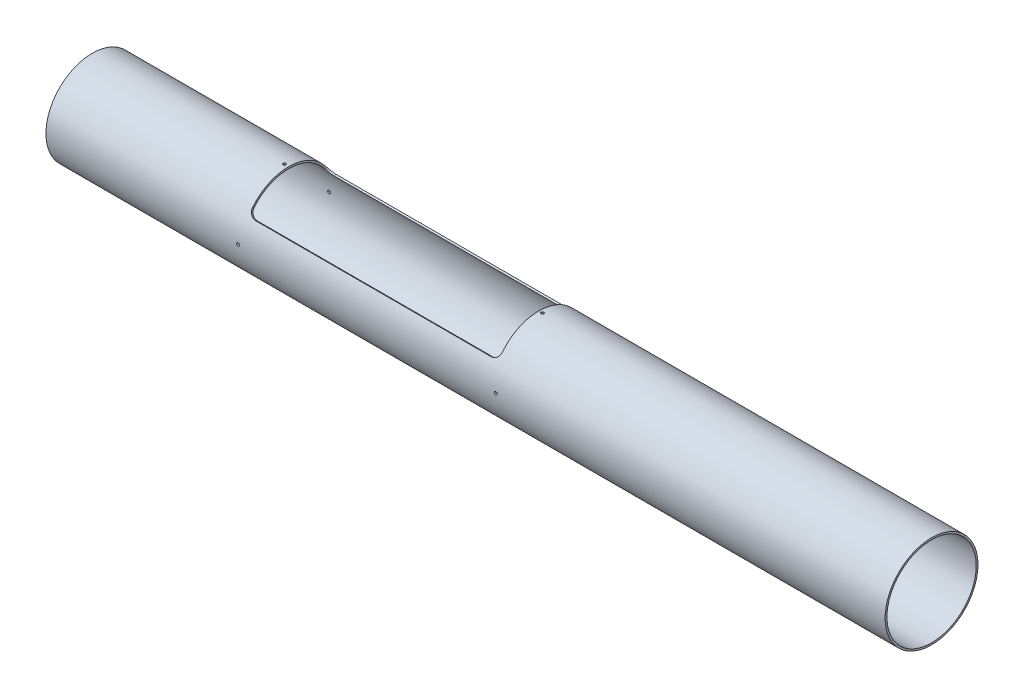
SolidWorks part; units mm, degrees
material "E-Glass Fiber"
ref_plane "Ön Düzlem" through (0, 0, 0) normal (0, 0, 1) x (1, 0, 0)
ref_plane "Üst Düzlem" through (0, 0, 0) normal (0, 1, 0) x (1, 0, 0)
ref_plane "Sağ Düzlem" through (0, 0, 0) normal (1, 0, 0) x (0, 0, -1)
sketch "Sketch1" plane through (0, 0, 0) normal (1, 0, 0) x (0, 0, -1)
  circle A0 centre (0, 0) radius 65
  circle A1 centre (0, 0) radius 62.5
  dimension "D1" = 2.5
  dimension "D2" = 130
  dimension "D3" = 125
extrude "Boss-Extrude1" add sketch "Sketch1" along normal mid plane 1175
sketch "Sketch3" plane through (0, 0, 0) normal (1, 0, 0) x (0, 0, -1)
  line L0 (0, -65) -> (0, 65) construction
  line L1 (0, 0) -> (56.2917, 32.5) construction
  line L2 (0, 0) -> (-56.2917, 32.5) construction
  line L5 (-56.2917, 32.5) -> (-54.1266, 31.25)
  line L6 (56.2917, 32.5) -> (54.1266, 31.25)
  circle A0 centre (0, 0) radius 65 construction
  arc A2 (-56.2917, 32.5) -> (56.2917, 32.5) centre (0, 0) cw
  arc A3 (-54.1266, 31.25) -> (54.1266, 31.25) centre (0, 0) cw
  circle A5 centre (0, 0) radius 62.5 construction
  dimension "D1" = 120
  dimension "D3" = 125
  dimension "D4" = 130
  dimension "D2" = 60
extrude "Cut-Extrude1" cut sketch "Sketch3" against normal blind 312.5 and the other way blind 37.5
fillet "Fillet1" radius 10 4 edges at (37.5, 31.875, 55.2091) (37.5, 31.875, -55.2091) (-312.5, 31.875, -55.2091) (-312.5, 31.875, 55.2091)
sketch "Sketch5" plane through (0, 0, 0) normal (0, 1, 0) x (1, 0, 0)
  line L2 (-587.5, 0) -> (-318.5, 0) construction
  line L3 (-587.5, 65) -> (-587.5, -65) construction
  line L5 (-318.5, 0) -> (-312.5, 0) construction
  line L6 (-312.5, 0) -> (37.5, 0) construction
  line L7 (37.5, 50.6215) -> (37.5, -50.6215) construction
  line L8 (37.5, 0) -> (42.5, 0) construction
  line L9 (42.5, 0) -> (587.5, 0) construction
  line L10 (587.5, -65) -> (587.5, 65) construction
  circle A0 centre (-318.5, 0) radius 2
  circle A1 centre (42.5, 0) radius 2
  dimension "D4" = 4
  dimension "D1" = 545
  dimension "D2" = 350
  dimension "D3" = 6
extrude "Cut-Extrude2" cut sketch "Sketch5" against normal mid plane 200
sketch "Sketch6" plane through (0, 0, 0) normal (0, 0, 1) x (1, 0, 0)
  line L0 (-307.5, 0) -> (-318.5, 0) construction
  line L1 (40.5, 65) -> (44.5, 65) construction
  line L3 (42.5, 0) -> (587.5, 0) construction
  line L4 (587.5, -65) -> (587.5, 65) construction
  line L5 (-318.5, 0) -> (-587.5, 0) construction
  line L6 (-587.5, 65) -> (-587.5, -65) construction
  line L7 (42.5, 65) -> (42.5, 0) construction
  line L8 (-320.5, 65) -> (-316.5, 65) construction
  line L9 (-318.5, 65) -> (-318.5, 0) construction
  circle A0 centre (-318.5, 0) radius 2
  circle A1 centre (42.5, 0) radius 2
  point P19 (42.5, 65)
  point P20 (0, 0)
  point P21 (0, 0)
  point P22 (0, 0)
  dimension "D5" = 4
  dimension "D1" = 269
  dimension "D2" = 545
  dimension "D3" = 350
  dimension "D4" = 1175
extrude "Cut-Extrude3" cut sketch "Sketch6" against normal mid plane 271
